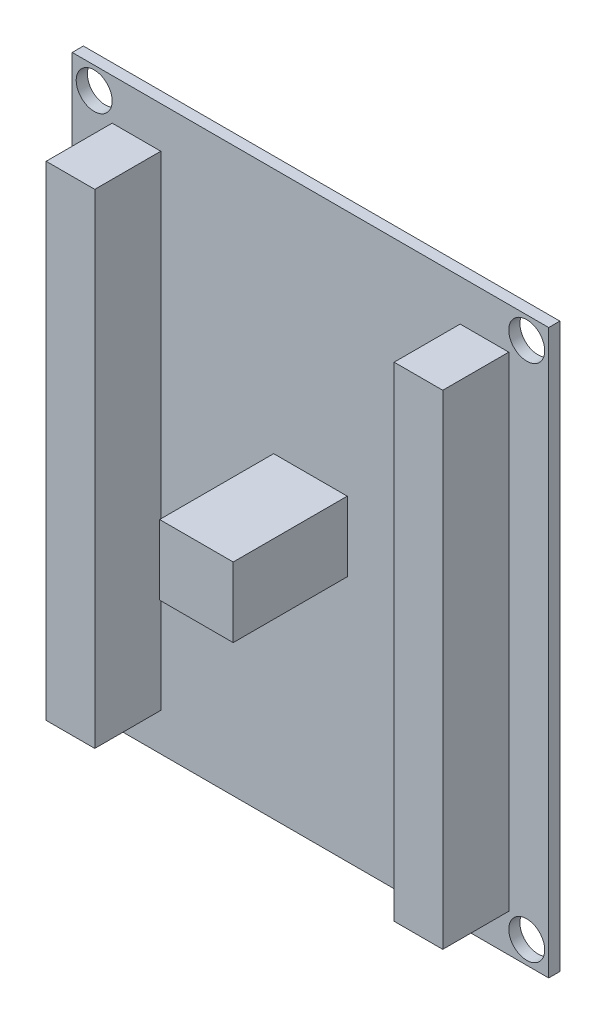
SolidWorks part; units mm, degrees
ref_plane "Front Plane" through (0, 0, 0) normal (0, 0, 1) x (1, 0, 0)
ref_plane "Top Plane" through (0, 0, 0) normal (0, 1, 0) x (1, 0, 0)
ref_plane "Right Plane" through (0, 0, 0) normal (1, 0, 0) x (0, 0, -1)
sketch "Sketch1" plane through (0, 0, 0) normal (0, 0, 1) x (1, 0, 0)
  line L1 (-33.13, -39.17) -> (33.13, -39.17)
  line L2 (-33.13, -39.17) -> (-33.13, 39.17)
  line L3 (-33.13, 39.17) -> (33.13, 39.17)
  line L4 (33.13, -39.17) -> (33.13, 39.17)
  line L5 (-33.13, -39.17) -> (33.13, 39.17) construction
  line L6 (-33.13, 39.17) -> (33.13, -39.17) construction
  point P0 (0, 0)
  dimension "D1" = 66.26
  dimension "D2" = 78.34
extrude "Boss-Extrude1" add sketch "Sketch1" along normal blind 1.55
sketch "Sketch2" plane through (0, 0, 1.55) normal (0, 0, 1) x (1, 0, 0)
  line L0 (-33.13, 35.1381) -> (-32.63, 35.1381) construction
  line L1 (-33.13, 39.17) -> (-33.13, -39.17) construction
  line L2 (-28.4205, 39.17) -> (-28.4205, 38.57) construction
  line L3 (33.13, 39.17) -> (-33.13, 39.17) construction
  line L4 (-28.4205, 38.57) -> (-33.4795, 38.57) construction
  line L5 (-32.63, 35.1381) -> (-32.63, 38.57) construction
  circle A0 centre (-30.0764, 36.0902) radius 2.5
  dimension "D3" = 5
  dimension "D1" = 0.5
  dimension "D2" = 0.6
extrude "Cut-Extrude1" cut sketch "Sketch2" against normal blind 16.55
sketch "Sketch3" plane through (0, 0, 1.55) normal (0, 0, 1) x (1, 0, 0)
  line L0 (0, 39.17) -> (0, -39.17) construction
  line L1 (33.13, 39.17) -> (-33.13, 39.17) construction
  line L2 (-33.13, -39.17) -> (33.13, -39.17) construction
  line L3 (-30.0764, 38.5902) -> (-30.0764, -39.17) construction
  line L4 (-33.13, 39.17) -> (-33.13, -39.17) construction
  circle A0 centre (-30.0764, 36.0902) radius 2.5 construction
  circle A1 centre (-30.0764, -36.07) radius 2.5
  dimension "D1" = 3.1
  dimension "D2" = 3.0536
extrude "Cut-Extrude2" cut sketch "Sketch3" against normal blind 16.55 contours A1
ref_plane "Plane1" through (0, 0, 0) normal (1, 0, 0) x (0, 0, -1)
mirror "Mirror1" about plane through (0, 0, 0) normal (1, 0, 0) of "Cut-Extrude1", "Cut-Extrude2"
sketch "Sketch4" plane through (0, 0, 1.55) normal (0, 0, 1) x (1, 0, 0)
  line L0 (-33.13, -36.07) -> (-27.5764, -36.07) construction
  line L1 (-20.8164, 33.43) -> (-27.5764, 33.43) construction
  line L2 (-33.13, 39.17) -> (-33.13, -39.17) construction
  line L3 (-27.5764, -39.17) -> (-27.5764, -33.91) construction
  line L4 (-33.13, -39.17) -> (33.13, -39.17) construction
  line L5 (-27.5764, -33.91) -> (-20.8164, -33.91) construction
  line L6 (-20.8164, -33.91) -> (-20.8164, 33.43) construction
  line L7 (-27.5764, 33.43) -> (-27.5764, -33.91) construction
  line L8 (-27.5764, 33.43) -> (-20.8164, 33.43)
  line L9 (-20.8164, 33.43) -> (-20.8164, -33.91)
  line L10 (-20.8164, -33.91) -> (-27.5764, -33.91)
  line L11 (-27.5764, -33.91) -> (-27.5764, 33.43)
  line L12 (-27.5764, 33.43) -> (-27.5764, -33.91)
  circle A1 centre (-30.0764, -36.07) radius 2.5 construction
extrude "Boss-Extrude2" add sketch "Sketch4" along normal blind 9.18 contours L11 L10 L9 L8
ref_plane "Plane3" through (0, 0, 0) normal (1, 0, 0) x (0, 0, -1)
mirror "Mirror2" about plane through (0, 0, 0) normal (1, 0, 0) of "Boss-Extrude2"
sketch "Sketch7" plane through (0, 0, 1.55) normal (0, 0, 1) x (1, 0, 0)
  line L0 (0, 0) -> (0, 39.17)
  line L1 (33.13, 39.17) -> (-33.13, 39.17) construction
  line L3 (-5.1164, -4.8554) -> (5.1164, -4.8554)
  line L4 (-5.1164, -4.8554) -> (-5.1164, 4.8554)
  line L5 (-5.1164, 4.8554) -> (5.1164, 4.8554)
  line L6 (5.1164, -4.8554) -> (5.1164, 4.8554)
  line L7 (-5.1164, -4.8554) -> (5.1164, 4.8554) construction
  line L8 (-5.1164, 4.8554) -> (5.1164, -4.8554) construction
extrude "Boss-Extrude3" add sketch "Sketch7" along normal blind 15.86
